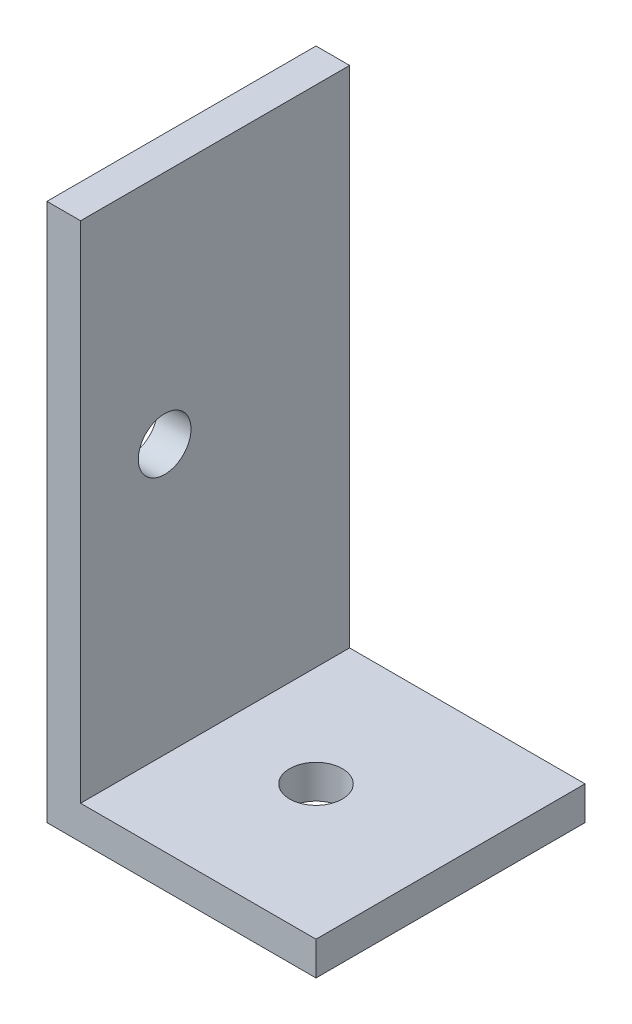
SolidWorks part; units mm, degrees
ref_plane "Front Plane" through (0, 0, 0) normal (0, 0, 1) x (1, 0, 0)
ref_plane "Top Plane" through (0, 0, 0) normal (0, 1, 0) x (1, 0, 0)
ref_plane "Right Plane" through (0, 0, 0) normal (1, 0, 0) x (0, 0, -1)
sketch "Sketch1" plane through (0, 0, 0) normal (0, 0, 1) x (1, 0, 0)
  line L0 (0, 0) -> (0, 50.8)
  line L1 (0, 50.8) -> (3.175, 50.8)
  line L2 (3.175, 50.8) -> (3.175, 3.175)
  line L3 (3.175, 3.175) -> (25.4, 3.175)
  line L4 (25.4, 3.175) -> (25.4, 0)
  line L5 (25.4, 0) -> (0, 0)
  dimension "D1" = 3.175
  dimension "D2" = 50.8
  dimension "D3" = 25.4
extrude "Boss-Extrude1" add sketch "Sketch1" along normal mid plane 25.4
sketch "Sketch2" plane through (0, 3.175, 0) normal (0, 1, 0) x (1, 0, 0)
  line L1 (0, -12.7) -> (25.4, -12.7) construction
  line L2 (25.4, -12.7) -> (25.4, 12.7) construction
  circle A0 centre (12.7, 0) radius 2.4892
  point P4 (12.7, -12.7)
  point P7 (25.4, 0)
  dimension "D1" = 4.9784
extrude "Cut-Extrude1" cut sketch "Sketch2" against normal through all
sketch "Sketch3" plane through (3.175, 0, 0) normal (1, 0, 0) x (0, 0, -1)
  line L0 (-12.7, 3.175) -> (-12.7, 50.8) construction
  line L2 (-12.7, 0) -> (12.7, 0) construction
  circle A0 centre (-4.7625, 28.575) radius 2.4892
  dimension "D1" = 4.9784
  dimension "D3" = 28.575
  dimension "D2" = 7.9375
extrude "Cut-Extrude2" cut sketch "Sketch3" against normal through all
